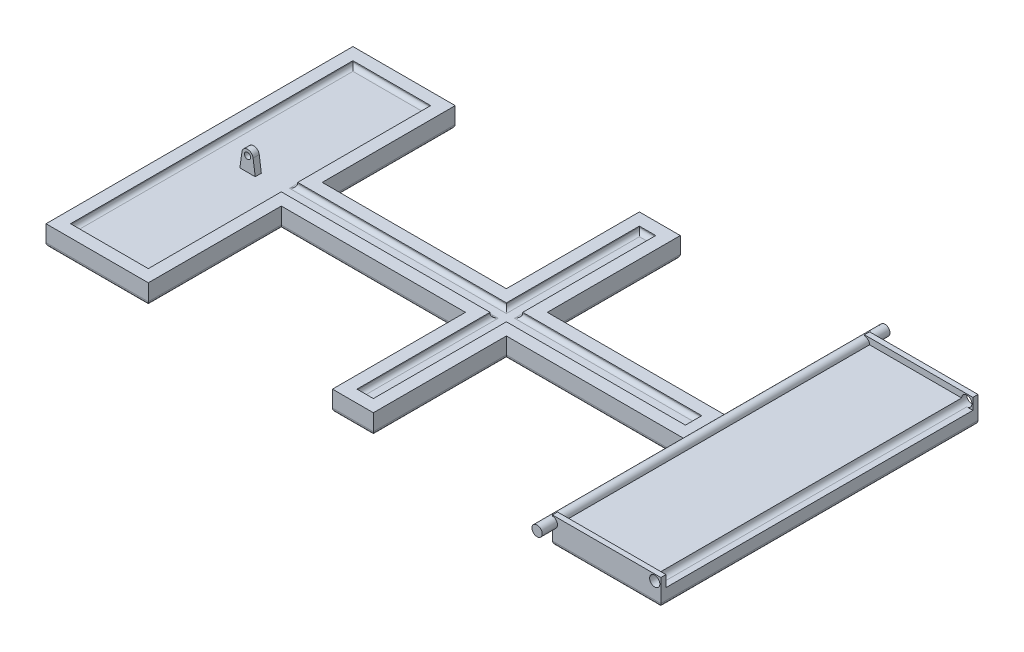
SolidWorks part; units mm, degrees
ref_plane "Front Plane" through (0, 0, 0) normal (0, 0, 1) x (1, 0, 0)
ref_plane "Top Plane" through (0, 0, 0) normal (0, 1, 0) x (1, 0, 0)
ref_plane "Right Plane" through (0, 0, 0) normal (1, 0, 0) x (0, 0, -1)
sketch "Sketch3" plane through (0, 0, 0) normal (0, 1, 0) x (1, 0, 0)
  line L0 (50, 150) -> (50, 85)
  line L1 (0, 0) -> (300, 0)
  line L2 (0, 0) -> (0, 150)
  line L3 (0, 150) -> (300, 150)
  line L4 (300, 0) -> (300, 150)
  line L5 (250, 150) -> (250, 85)
  line L6 (0, 75) -> (300, 75) construction
  line L7 (150, 150) -> (150, 0) construction
  line L8 (50, 85) -> (140, 85)
  line L9 (140, 150) -> (140, 85)
  line L10 (160, 85) -> (250, 85)
  line L11 (160, 150) -> (160, 85)
  line L12 (250, 0) -> (250, 65)
  line L13 (160, 65) -> (250, 65)
  line L14 (160, 0) -> (160, 65)
  line L15 (140, 0) -> (140, 65)
  line L16 (50, 65) -> (140, 65)
  line L17 (50, 0) -> (50, 65)
  dimension "D1" = 300
  dimension "D2" = 150
  dimension "D3" = 50
  dimension "D4" = 50
  dimension "D5" = 10
  dimension "D6" = 10
  dimension "D7" = 10
extrude "Boss-Extrude1" add sketch "Sketch3" against normal blind 10 contours L1 L17 L16 L15 L14 L13 L12 L4 L3 L5 L10 L11 L9 L8 L0 L2
sketch "Sketch4" plane through (0, 0, 0) normal (0, 0, 1) x (1, 0, 0)
  circle A0 centre (250, 0) radius 2.5
  dimension "D1" = 5
extrude "Boss-Extrude2" add sketch "Sketch4" along normal blind 10 and the other way offset from surface (160 mm away) 10 other way up to face at (275, -5, -150)
sketch "Sketch5" plane through (0, 0, 0) normal (0, 1, 0) x (1, 0, 0)
  line L0 (44, 144) -> (6, 144)
  line L1 (6, 144) -> (6, 6)
  line L2 (6, 6) -> (44, 6)
  line L3 (44, 6) -> (44, 71)
  line L4 (44, 71) -> (146, 71)
  line L5 (146, 71) -> (146, 6)
  line L6 (146, 6) -> (154, 6)
  line L7 (154, 6) -> (154, 71)
  line L8 (154, 71) -> (241.5, 71)
  line L9 (241.5, 71) -> (241.5, 79)
  line L10 (241.5, 79) -> (154, 79)
  line L11 (154, 79) -> (154, 144)
  line L12 (154, 144) -> (146, 144)
  line L13 (146, 144) -> (146, 79)
  line L14 (146, 79) -> (44, 79)
  line L15 (44, 79) -> (44, 144)
extrude "Cut-Extrude2" cut sketch "Sketch5" against normal blind 2.5
fillet "Fillet1" radius 2 16 edges at (95, -2.5, -79) (146, -2.5, -111.5) (150, -2.5, -144) (154, -2.5, -111.5) (197.75, -2.5, -79) (241.5, -2.5, -75) (197.75, -2.5, -71) (154, -2.5, -38.5) (150, -2.5, -6) (146, -2.5, -38.5) (95, -2.5, -71) (44, -2.5, -38.5) (25, -2.5, -6) (6, -2.5, -75) (25, -2.5, -144) (44, -2.5, -111.5)
sketch "Sketch6" plane through (0, 0, 0) normal (0, 0, 1) x (1, 0, 0)
  line L0 (297, 0) -> (297, 3)
  line L1 (252.5, 0) -> (300, 0) construction
  line L2 (297, 3) -> (303, 3)
  line L3 (303, 3) -> (303, -3)
  line L4 (303, -3) -> (300, -3)
  line L5 (300, -10) -> (300, 0) construction
  circle A0 centre (300, 0) radius 2.5
  dimension "D1" = 5
  dimension "D2" = 3
  dimension "D3" = 6
  dimension "D4" = 6
  dimension "D5" = 3
ref_plane "Plane1" through (0, 0, -75) normal (0, 0, 1) x (1, 0, 0)
extrude "Boss-Extrude6" add sketch "Sketch6" along normal blind 2.5
mirror "Mirror2" about plane through (0, 0, -75) normal (0, 0, 1) of "Boss-Extrude6"
sketch "Sketch7" plane through (300, 0, 0) normal (1, 0, 0) x (0, 0, -1)
  line L0 (0, -3) -> (150, -3)
  line L10 (150, 0) -> (0, 0)
  line L11 (0, 0) -> (0, -2.5)
  line L12 (0, -2.5) -> (0, -3)
  line L13 (0, -3) -> (-2.5, -3)
  line L14 (-2.5, -3) -> (-2.5, -10)
  line L15 (-2.5, -10) -> (152.5, -10)
  line L16 (152.5, -10) -> (152.5, -3)
  line L17 (152.5, -3) -> (150, -3)
  line L18 (150, -3) -> (150, -2.5)
  line L19 (150, -2.5) -> (150, 0)
  line L20 (150, 0) -> (0, 0)
  line L21 (0, 0) -> (0, -2.5)
  line L22 (0, -2.5) -> (0, -3)
  line L23 (0, -3) -> (-2.5, -3)
  line L24 (-2.5, -3) -> (-2.5, -10)
  line L25 (-2.5, -10) -> (152.5, -10)
  line L26 (152.5, -10) -> (152.5, -3)
  line L27 (152.5, -3) -> (150, -3)
  line L28 (150, -3) -> (150, -2.5)
  line L29 (150, -2.5) -> (150, 0)
  line M14 (0, -3) -> (-2.5, -3)
  line M15 (-2.5, -3) -> (-2.5, -10)
  line M16 (-2.5, -10) -> (152.5, -10)
  line M17 (152.5, -10) -> (152.5, -3)
  line M18 (152.5, -3) -> (150, -3)
  dimension "D1" = 0
extrude "Boss-Extrude7" add sketch "Sketch7" along normal up to surface (3 mm away) contours L0 M14 M15 M16 M17 M18 up to face at (303, 0, 1.25)
sketch "Sketch8" plane through (297, 0, 0) normal (-1, 0, 0) x (0, 0, 1)
  line L4 (0, 3) -> (0, 0)
  line L5 (0, 0) -> (2.5, 0)
  line L6 (2.5, 0) -> (2.5, 3)
  line L7 (2.5, 3) -> (0, 3)
  line L8 (0, 3) -> (0, 0)
  line L9 (0, 0) -> (2.5, 0)
  line L10 (2.5, 0) -> (2.5, 3)
  line L11 (2.5, 3) -> (0, 3)
  dimension "D1" = 0
extrude "Boss-Extrude8" add sketch "Sketch8" along normal up to surface (47 mm away) up to face at (250, -6.25, -31.25)
mirror "Mirror3" about plane through (0, 0, -75) normal (0, 0, 1) of "Boss-Extrude8"
sketch "Sketch9" plane through (0, 0, 2.5) normal (0, 0, 1) x (1, 0, 0)
  circle A0 centre (300, 0) radius 2.5 construction
  circle A1 centre (300, 0) radius 2.5
extrude "Cut-Extrude3" cut sketch "Sketch9" against normal through all
sketch "Sketch10" plane through (0, -3, 0) normal (0, 1, 0) x (1, 0, 0)
  line L4 (300, 0) -> (303, 0)
  line L5 (303, 0) -> (303, 150)
  line L6 (303, 150) -> (300, 150)
  line L7 (300, 150) -> (300, 0)
  line L8 (300, 0) -> (303, 0)
  line L9 (303, 0) -> (303, 150)
  line L10 (303, 150) -> (300, 150)
  line L11 (300, 150) -> (300, 0)
  dimension "D1" = 0
extrude "Boss-Extrude9" add sketch "Sketch10" along normal up to vertex (0.5 mm away)
fillet "Fillet2" radius 2 20 edges at (50, -10, -32.5) (95, -10, -65) (140, -10, -32.5) (150, -10, 0) (160, -10, -32.5) (205, -10, -65) (250, -10, -31.25) (276.5, -10, 2.5) (303, -10, -75) (276.5, -10, -152.5) (250, -10, -118.75) (205, -10, -85) (160, -10, -117.5) (150, -10, -150) (140, -10, -117.5) (95, -10, -85) (50, -10, -117.5) (25, -10, -150) (0, -10, -75) (25, -10, 0)
sketch "Sketch11" plane through (0, -2.5, 0) normal (0, 1, 0) x (1, 0, 0)
  line L1 (8, 75) -> (25, 75) construction
  line L2 (25, 142) -> (25, 8) construction
  line L4 (21.25, 76.5) -> (28.75, 76.5)
  line L5 (21.25, 76.5) -> (21.25, 73.5)
  line L6 (21.25, 73.5) -> (28.75, 73.5)
  line L7 (28.75, 76.5) -> (28.75, 73.5)
  line L16 (148, 142) -> (148, 77)
  line L17 (148, 77) -> (42, 77)
  line L18 (42, 77) -> (42, 142)
  line L19 (42, 142) -> (8, 142)
  line L20 (8, 142) -> (8, 8)
  line L21 (8, 8) -> (42, 8)
  line L22 (42, 8) -> (42, 73)
  line L23 (42, 73) -> (148, 73)
  line L24 (148, 73) -> (148, 8)
  line L25 (148, 8) -> (152, 8)
  line L26 (152, 8) -> (152, 73)
  line L27 (152, 73) -> (239.5, 73)
  line L28 (239.5, 73) -> (239.5, 77)
  line L29 (239.5, 77) -> (152, 77)
  line L30 (152, 77) -> (152, 142)
  line L31 (152, 142) -> (148, 142)
  line L34 (42, 77) -> (42, 142)
  line L35 (42, 142) -> (8, 142)
  line L36 (8, 142) -> (8, 8)
  line L37 (8, 8) -> (42, 8)
  line L38 (42, 8) -> (42, 73)
  line L41 (148, 8) -> (152, 8)
  line L44 (239.5, 73) -> (239.5, 77)
  line L47 (152, 142) -> (148, 142)
  dimension "D2" = 3
  dimension "D3" = 7.5
  dimension "D1" = 0
extrude "Boss-Extrude10" add sketch "Sketch11" along normal blind 10 contours L7 L4 L5 L6
sketch "Sketch12" plane through (0, 0, -73.5) normal (0, 0, 1) x (1, 0, 0)
  line L0 (25, -2.5) -> (25, 7.5) construction
  line L1 (28.75, -2.5) -> (27.7238, 4.8788)
  line L2 (21.25, -2.5) -> (22.2762, 4.8788)
  line L3 (21.25, -2.5) -> (28.75, -2.5) construction
  line L4 (21.25, -2.5) -> (28.75, -2.5)
  line L5 (28.75, -2.5) -> (28.75, 7.5)
  line L6 (28.75, 7.5) -> (21.25, 7.5)
  line L7 (21.25, 7.5) -> (21.25, -2.5)
  line L9 (28.75, -2.5) -> (28.75, 7.5)
  line L10 (28.75, 7.5) -> (21.25, 7.5)
  line L11 (21.25, 7.5) -> (21.25, -2.5)
  circle A0 centre (25, 4.5) radius 1.5
  arc A1 (27.7238, 4.8788) -> (22.2762, 4.8788) centre (25, 4.5) ccw
  dimension "D2" = 3
  dimension "D3" = 5.5
  dimension "D4" = 7
  dimension "D1" = 0
extrude "Cut-Extrude4" cut sketch "Sketch12" against normal blind 10
